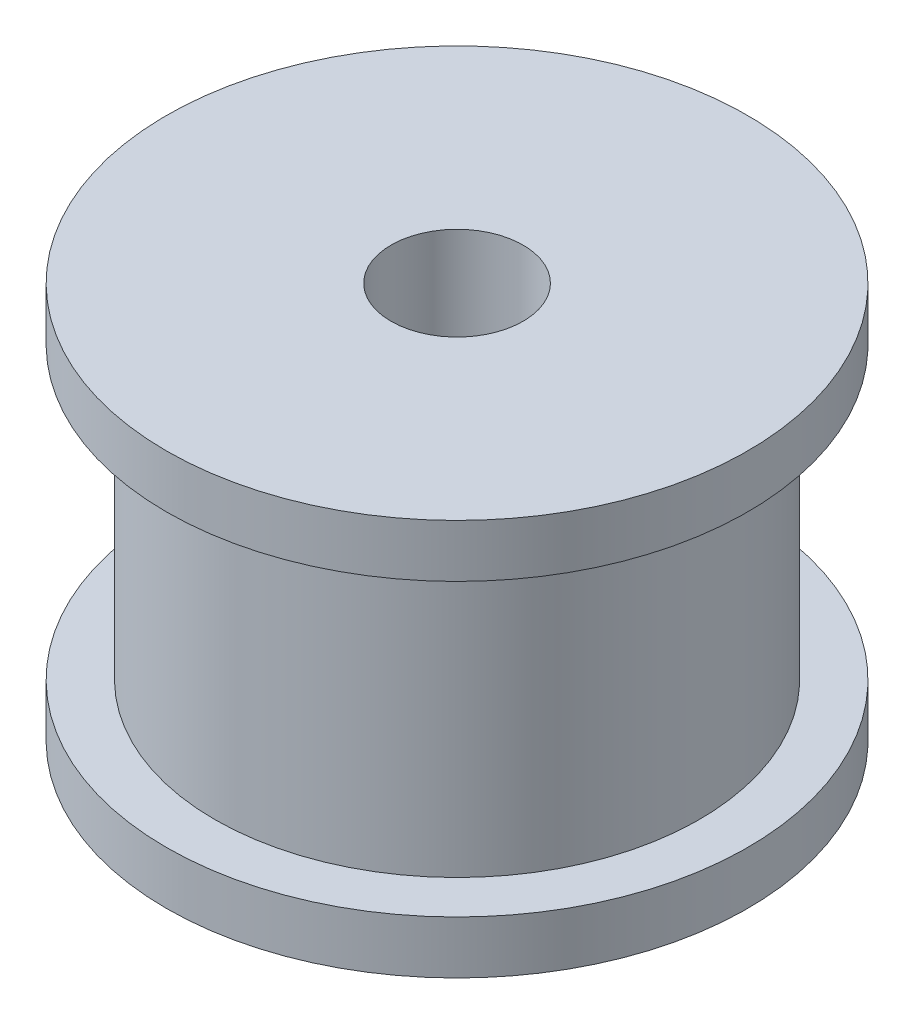
SolidWorks part; units mm, degrees
material "AISI 304"
ref_plane "前视基准面" through (0, 0, 0) normal (0, 0, 1) x (1, 0, 0)
ref_plane "上视基准面" through (0, 0, 0) normal (0, 1, 0) x (1, 0, 0)
ref_plane "右视基准面" through (0, 0, 0) normal (1, 0, 0) x (0, 0, -1)
other "Configuration Table"
sketch "草图1" plane through (0, 0, 0) normal (0, 1, 0) x (1, 0, 0)
  circle A0 centre (0, 0) radius 11
  dimension "D1" = 22
extrude "凸台-拉伸1" add sketch "草图1" along normal blind 2
sketch "草图2" plane through (0, 2, 0) normal (0, 1, 0) x (1, 0, 0)
  circle A0 centre (0, 0) radius 9.17
  dimension "D1" = 18.34
extrude "凸台-拉伸2" add sketch "草图2" along normal blind 11
sketch "草图3" plane through (0, 13, 0) normal (0, 1, 0) x (1, 0, 0)
  circle A0 centre (0, 0) radius 11
  dimension "D1" = 22
extrude "凸台-拉伸3" add sketch "草图3" along normal blind 2
sketch "草图4" plane through (0, 15, 0) normal (0, 1, 0) x (1, 0, 0)
  circle A0 centre (0, 0) radius 2.5
  dimension "D1" = 5
extrude "切除-拉伸1" cut sketch "草图4" against normal blind 26
